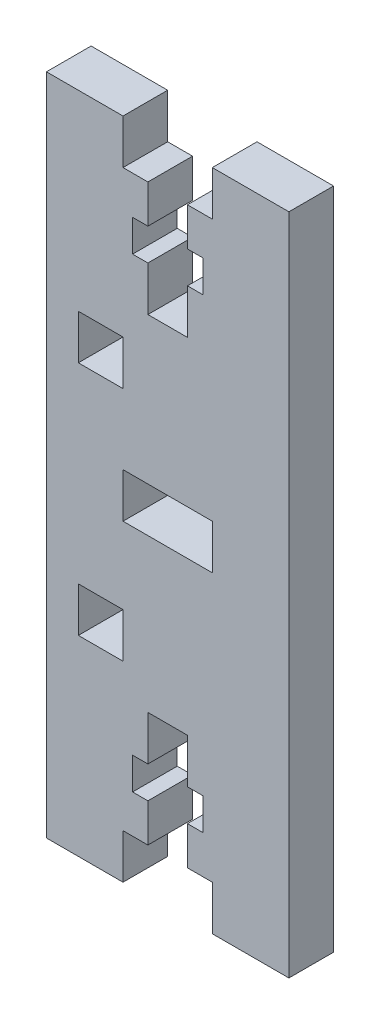
SolidWorks part; units mm, degrees
material "Balsa"
ref_plane "Front Plane" through (0, 0, 0) normal (0, 0, 1) x (1, 0, 0)
ref_plane "Top Plane" through (0, 0, 0) normal (0, 1, 0) x (1, 0, 0)
ref_plane "Right Plane" through (0, 0, 0) normal (1, 0, 0) x (0, 0, -1)
sketch "Sketch1" plane through (0, 0, 0) normal (0, 0, 1) x (1, 0, 0)
  line L0 (3.5, 26) -> (3.5, 22.5)
  line L1 (-9.5, -26) -> (9.5, -26) construction
  line L2 (-9.5, -26) -> (-9.5, 26)
  line L3 (-9.5, 26) -> (9.5, 26) construction
  line L4 (9.5, -26) -> (9.5, 26)
  line L5 (0, 26) -> (0, -26) construction
  line L6 (-9.5, 0) -> (9.5, 0) construction
  line L7 (3.5, 22.5) -> (1.55, 22.5)
  line L8 (1.55, 22.5) -> (1.55, 19.5)
  line L9 (1.55, 19.5) -> (2.75, 19.5)
  line L10 (2.75, 19.5) -> (2.75, 17)
  line L11 (2.75, 17) -> (1.55, 17)
  line L12 (1.55, 17) -> (1.55, 13.5)
  line L13 (1.55, 13.5) -> (-1.55, 13.5)
  line L14 (-1.55, 17) -> (-1.55, 13.5)
  line L15 (-2.75, 17) -> (-1.55, 17)
  line L16 (-2.75, 19.5) -> (-2.75, 17)
  line L17 (-1.55, 19.5) -> (-2.75, 19.5)
  line L18 (-1.55, 22.5) -> (-1.55, 19.5)
  line L19 (-3.5, 22.5) -> (-1.55, 22.5)
  line L20 (-3.5, 26) -> (-3.5, 22.5)
  line L21 (9.5, 26) -> (3.5, 26)
  line L22 (-3.5, 26) -> (-9.5, 26)
  line L23 (3.5, -26) -> (3.5, -22.5)
  line L24 (3.5, -22.5) -> (1.55, -22.5)
  line L25 (1.55, -22.5) -> (1.55, -19.5)
  line L26 (1.55, -19.5) -> (2.75, -19.5)
  line L27 (2.75, -19.5) -> (2.75, -17)
  line L28 (2.75, -17) -> (1.55, -17)
  line L29 (1.55, -17) -> (1.55, -13.5)
  line L30 (1.55, -13.5) -> (-1.55, -13.5)
  line L31 (-1.55, -17) -> (-1.55, -13.5)
  line L32 (-2.75, -17) -> (-1.55, -17)
  line L33 (-2.75, -19.5) -> (-2.75, -17)
  line L34 (-1.55, -19.5) -> (-2.75, -19.5)
  line L35 (-1.55, -22.5) -> (-1.55, -19.5)
  line L36 (-3.5, -22.5) -> (-1.55, -22.5)
  line L37 (-3.5, -26) -> (-3.5, -22.5)
  line L38 (9.5, -26) -> (3.5, -26)
  line L39 (-3.5, -26) -> (-9.5, -26)
  line L40 (0, -4.9288) -> (0, 3.2808) construction
  point P0 (0, 0)
  point P14 (0, 13.5)
  dimension "D1" = 19
  dimension "D2" = 52
  dimension "D3" = 7
  dimension "D4" = 3.5
  dimension "D5" = 3.1
  dimension "D6" = 3
  dimension "D7" = 2.5
  dimension "D8" = 5.5
  dimension "D9" = 3.5
  dimension "D10" = 0
extrude "Boss-Extrude1" add sketch "Sketch1" along normal blind 3.5
sketch "Sketch2" plane through (0, 0, 0) normal (0, 0, -1) x (-1, 0, 0)
  line L0 (14.6938, 0) -> (-16.4931, 0) construction
  line L1 (3.5, -7.5) -> (3.5, 7.5) construction
  line L3 (3.5, -7.5) -> (7, -7.5)
  line L4 (3.5, -7.5) -> (3.5, -11)
  line L5 (3.5, -11) -> (7, -11)
  line L6 (7, -7.5) -> (7, -11)
  line L7 (7, 7.5) -> (7, 11)
  line L8 (3.5, 11) -> (7, 11)
  line L9 (3.5, 7.5) -> (3.5, 11)
  line L10 (3.5, 7.5) -> (7, 7.5)
  line L12 (3.5, -26) -> (3.5, -22.5) construction
  point P8 (3.5, 0)
  dimension "D1" = 15
  dimension "D2" = 3.5
  dimension "D3" = 3.5
extrude "Cut-Extrude1" cut sketch "Sketch2" against normal through all
sketch "Sketch3" plane through (0, 0, 0) normal (0, 0, -1) x (-1, 0, 0)
  line L0 (-1.55, -22.5) -> (-3.5, -22.5) construction
  line L1 (-3.5, -1.5) -> (3.5, -1.5)
  line L2 (-3.5, -1.5) -> (-3.5, 2)
  line L3 (-3.5, 2) -> (3.5, 2)
  line L4 (3.5, -1.5) -> (3.5, 2)
  line L5 (9.5, 26) -> (9.5, -26) construction
  point P6 (-2.525, -22.5)
  dimension "D1" = 21
  dimension "D2" = 3.5
  dimension "D3" = 7
  dimension "D4" = 6
extrude "Cut-Extrude2" cut sketch "Sketch3" against normal through all
